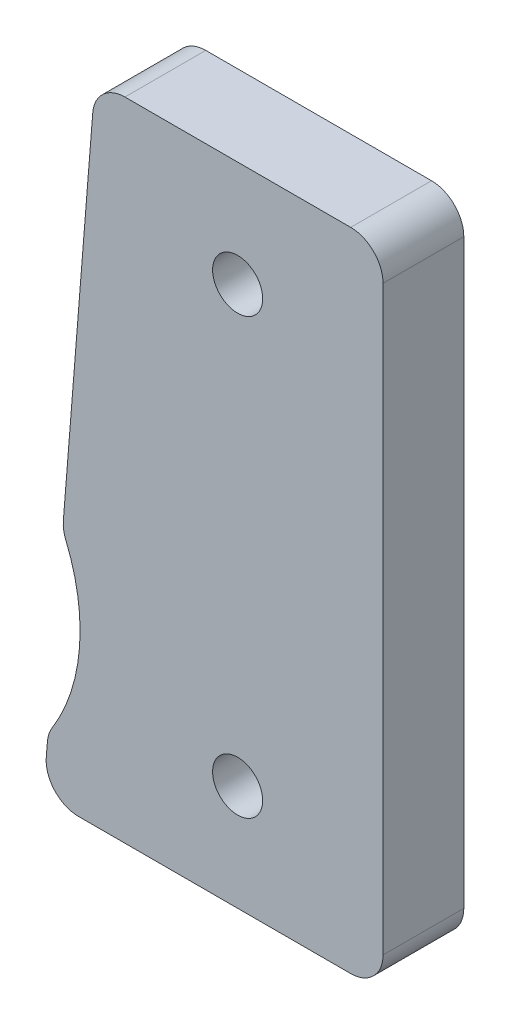
SolidWorks part; units mm, degrees
material "A-玻璃纤维"
ref_plane "前视基准面" through (0, 0, 0) normal (0, 0, 1) x (1, 0, 0)
ref_plane "上视基准面" through (0, 0, 0) normal (0, 1, 0) x (1, 0, 0)
ref_plane "右视基准面" through (0, 0, 0) normal (1, 0, 0) x (0, 0, -1)
other "Configuration Table"
sketch "草图1" plane through (0, 0, 0) normal (0, 0, 1) x (1, 0, 0)
  line L1 (-15, -20) -> (15, -20)
  line L2 (-15, -20) -> (-15, 20)
  line L3 (-15, 20) -> (15, 20)
  line L4 (15, -20) -> (15, 20)
  line L5 (-15, -20) -> (15, 20) construction
  line L6 (-15, 20) -> (15, -20) construction
  point P0 (0, 0)
  dimension "D1" = 40
  dimension "D2" = 30
extrude "凸台-拉伸1" add sketch "草图1" along normal blind 5
sketch "草图2" plane through (0, 0, 5) normal (0, 0, 1) x (1, 0, 0)
  line L1 (-8.8199, 20) -> (-12.0175, -20)
  line L2 (15, 20) -> (-15, 20) construction
  line L3 (-15, -20) -> (15, -20) construction
  line L4 (-12.0175, -20) -> (-15, -20)
  line L5 (-15, -20) -> (-15, 20)
  line L6 (-15, 20) -> (-8.8199, 20)
  dimension "D1" = 85.429
  dimension "D2" = 10.3856
extrude "切除-拉伸1" cut sketch "草图2" against normal blind 800
sketch "草图3" plane through (0, 0, 5) normal (0, 0, 1) x (1, 0, 0)
  circle A0 centre (0, 13.45) radius 1.55 construction
  circle A1 centre (0, -13.45) radius 1.55 construction
  circle A2 centre (0, 13.45) radius 1.55
  circle A3 centre (0, -13.45) radius 1.55
extrude "切除-拉伸2" cut sketch "草图3" against normal blind 10
fillet "圆角1" radius 2 4 edges at (-12.0175, -20, 2.5) (15, 20, 2.5) (-8.8199, 20, 2.5) (15, -20, 2.5)
sketch "草图4" plane through (0, 0, 5) normal (0, 0, 1) x (1, 0, 0)
  circle A0 centre (-21.25, -10) radius 3.1 construction
  circle A1 centre (-21.25, -10) radius 3.1 construction
  circle A2 centre (-21.25, -10) radius 11.5
  dimension "D1" = 23
extrude "切除-拉伸3" cut sketch "草图4" against normal blind 10
fillet "圆角2" radius 2 2 edges at (-11.7343, -16.4577, 2.5) (-10.8293, -5.136, 2.5)
sketch "草图5" plane through (0, 0, 5) normal (0, 0, 1) x (1, 0, 0)
  line L0 (-3, 9.45) -> (10, 9.45)
  line L1 (10, 9.45) -> (10, -9.45)
  line L2 (10, -9.45) -> (-3, -9.45)
  line L3 (-3, -9.45) -> (-3, 9.45)
  line L4 (15, -18) -> (15, 18) construction
  circle A0 centre (0, -13.45) radius 1.55 construction
  circle A1 centre (0, 13.45) radius 1.55 construction
  dimension "D1" = 4
  dimension "D2" = 4
  dimension "D3" = 5
  dimension "D4" = 3
extrude "切除-拉伸4" [suppressed] cut sketch "草图5" against normal blind 5
fillet "圆角3" [suppressed] radius 1.5
sketch "草图6" plane through (0, 0, 5) normal (0, 0, 1) x (1, 0, 0)
  line L0 (9, 20) -> (9, -20)
  line L1 (13, 20) -> (-6.9734, 20) construction
  line L2 (-9.8512, -20) -> (13, -20) construction
  line L3 (15, -18) -> (15, 18) construction
  dimension "D1" = 6
extrude "切除-拉伸5" cut sketch "草图6" against normal blind 5 and the other way through all
fillet "圆角4" radius 2 2 edges at (9, 20, 2.5) (9, -20, 2.5)
equation "\"D2@草图5\"=\"D1@草图5\""
